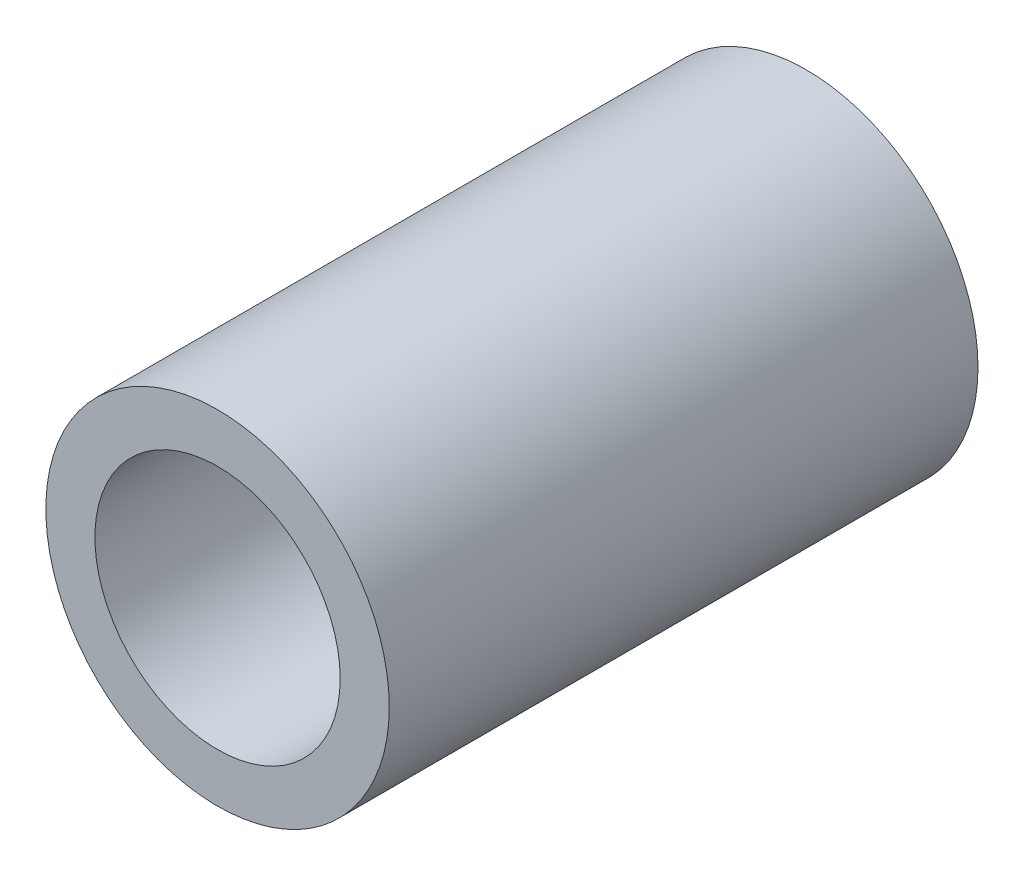
SolidWorks part; units mm, degrees
material "Pine"
ref_plane "Front Plane" through (0, 0, 0) normal (0, 0, 1) x (1, 0, 0)
ref_plane "Top Plane" through (0, 0, 0) normal (0, 1, 0) x (1, 0, 0)
ref_plane "Right Plane" through (0, 0, 0) normal (1, 0, 0) x (0, 0, -1)
sketch "Sketch1" plane through (0, 0, 0) normal (0, 0, 1) x (1, 0, 0)
  circle A0 centre (0, 0) radius 35
  circle A1 centre (0, 0) radius 20
  dimension "D1" = 40
  dimension "D2" = 70
extrude "Boss-Extrude1" add sketch "Sketch1" along normal blind 10
sketch "Sketch2" plane through (0, 0, 10) normal (0, 0, 1) x (1, 0, 0)
  circle A0 centre (0, 0) radius 25
  circle A1 centre (0, 0) radius 35
  dimension "D1" = 50
  dimension "D2" = 70
extrude "Boss-Extrude2" add sketch "Sketch2" along normal blind 110
